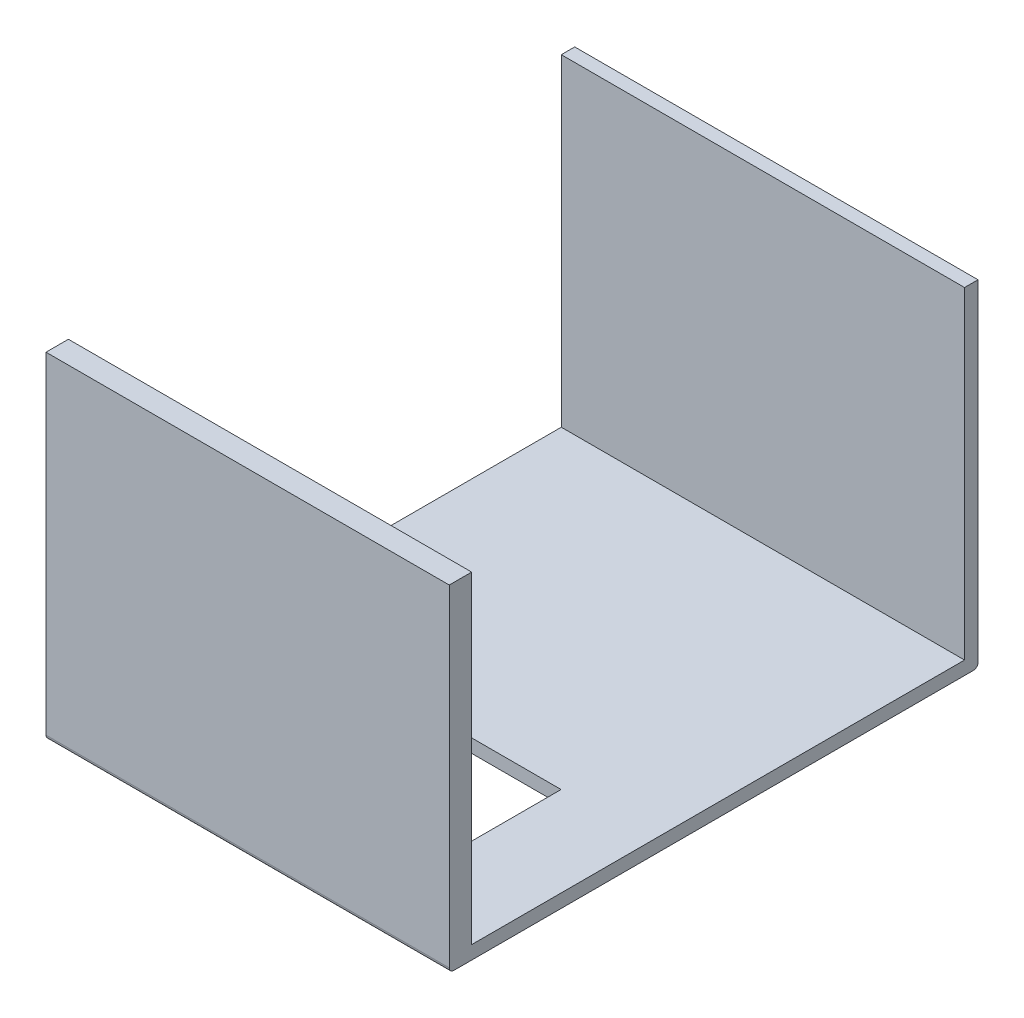
SolidWorks part; units mm, degrees
ref_plane "Plano frontal" through (0, 0, 0) normal (0, 0, 1) x (1, 0, 0)
ref_plane "Plano superior" through (0, 0, 0) normal (0, 1, 0) x (1, 0, 0)
ref_plane "Plano direito" through (0, 0, 0) normal (1, 0, 0) x (0, 0, -1)
sketch "Esboço1" plane through (0, 0, 0) normal (0, 1, 0) x (1, 0, 0)
  line L1 (0, 0) -> (90, 0)
  line L2 (0, 0) -> (0, 110)
  line L3 (0, 110) -> (90, 110)
  line L4 (90, 0) -> (90, 110)
extrude "Ressalto-extrusão1" add sketch "Esboço1" along normal blind 3
sketch "Esboço2" plane through (0, 3, 0) normal (0, 1, 0) x (1, 0, 0)
  line L4 (0, 0) -> (90, 0) construction
  line L5 (20, 0) -> (70, 0)
  line L6 (20, 0) -> (20, 39.9515)
  line L7 (20, 39.9515) -> (70, 39.9515)
  line L8 (70, 0) -> (70, 39.9515)
extrude "Corte-extrusão2" cut sketch "Esboço2" against normal through all
ref_plane "Plano1" through (20, 0, 0) normal (1, 0, 0) x (0, 0, -1)
sketch "Esboço4" plane through (0, 0, 0) normal (0, 0, 1) x (1, 0, 0)
  line L2 (0, 0) -> (90, 0)
  line L3 (0, 0) -> (0, 75)
  line L4 (0, 75) -> (90, 75)
  line L5 (90, 0) -> (90, 75)
extrude "Ressalto-extrusão2" add sketch "Esboço4" along normal blind 5
sketch "Esboço5" plane through (0, 0, -110) normal (0, 0, -1) x (-1, 0, 0)
  line L1 (-90, 0) -> (0, 0)
  line L2 (-90, 0) -> (-90, 75)
  line L3 (-90, 75) -> (0, 75)
  line L4 (0, 0) -> (0, 75)
extrude "Ressalto-extrusão3" add sketch "Esboço5" along normal blind 3
fillet "Filete5" radius 1 2 edges at (45, 0, -113) (45, 0, 5)
